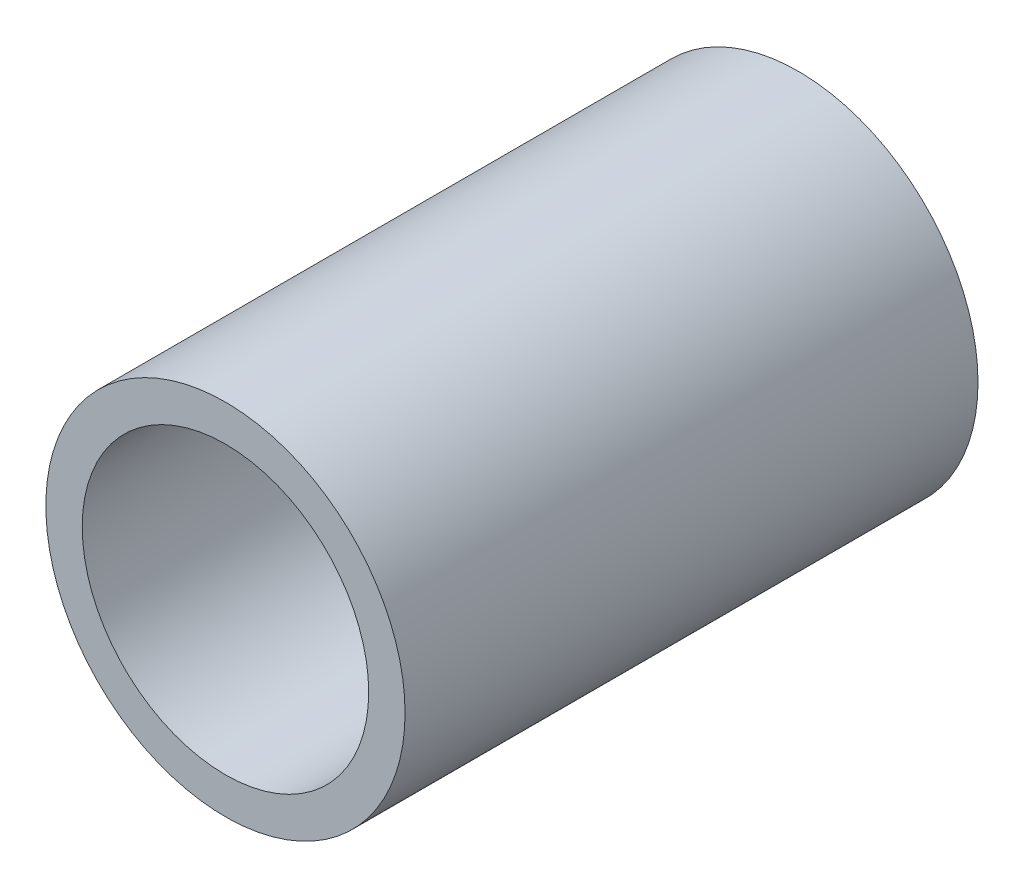
SolidWorks part; units mm, degrees
ref_plane "Front Plane" through (0, 0, 0) normal (0, 0, 1) x (1, 0, 0)
ref_plane "Top Plane" through (0, 0, 0) normal (0, 1, 0) x (1, 0, 0)
ref_plane "Right Plane" through (0, 0, 0) normal (1, 0, 0) x (0, 0, -1)
sketch "Sketch1" plane through (0, 0, 0) normal (0, 0, 1) x (1, 0, 0)
  circle A0 centre (0, 0) radius 7.9629
  circle A1 centre (0, 0) radius 6.35
  dimension "D1" = 15.9258
  dimension "ID" = 12.7
extrude "Extrude1" add sketch "Sketch1" along normal mid plane 25.4
sketch "Sketch2" plane through (0, 0, 0) normal (1, 0, 0) x (0, 0, -1)
  line L0 (-12.7, -6.35) -> (12.7, -6.35) construction
  line L3 (12.7, 6.35) -> (-12.7, 6.35) construction
  line L5 (-12.7, -6.35) -> (12.7, -6.35)
  line L6 (12.7, 6.35) -> (-12.7, 6.35)
sketch "Sketch4" plane through (0, 0, 12.7) normal (0, 0, 1) x (1, 0, 0)
  line L0 (0, 0) -> (-4.4901, 4.4901)
  line L1 (0, -15.7442) -> (0, 15.7442) construction
  circle A0 centre (0, 0) radius 6.35 construction
  dimension "D1" = 45
